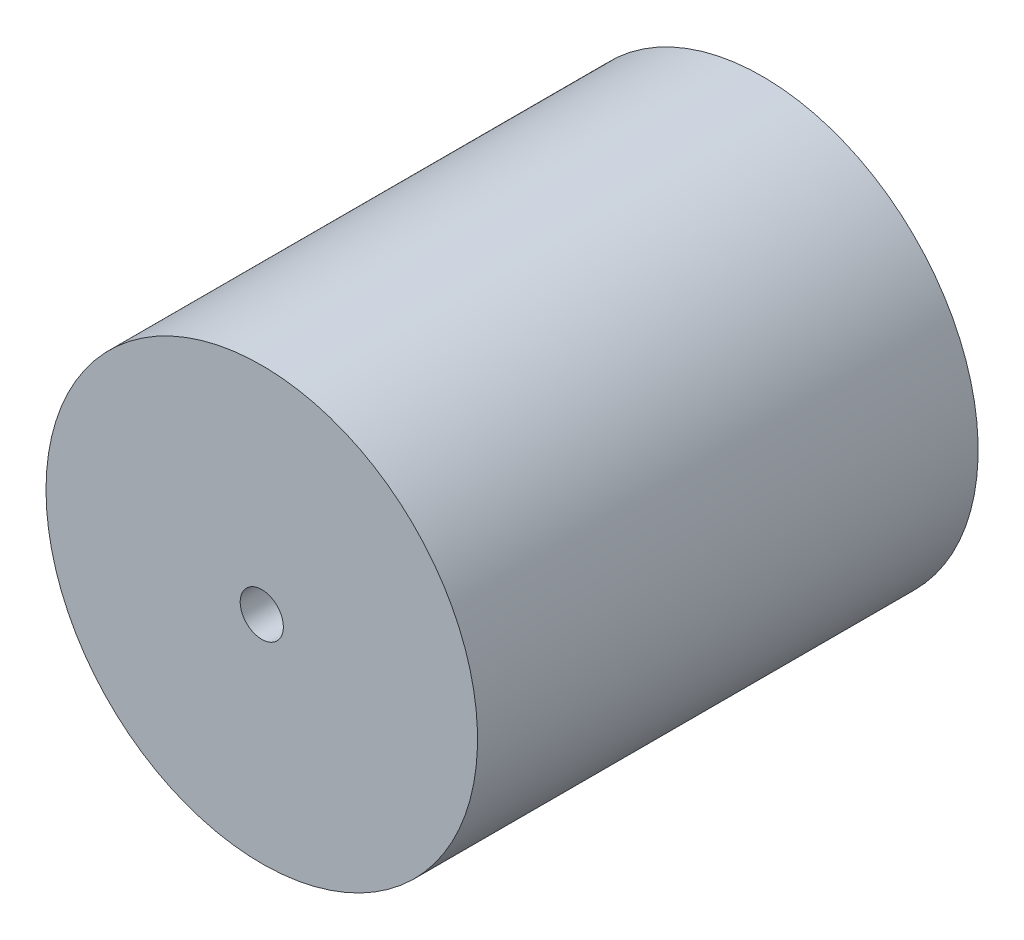
SolidWorks part; units mm, degrees
ref_plane "Front Plane" through (0, 0, 0) normal (0, 0, 1) x (1, 0, 0)
ref_plane "Top Plane" through (0, 0, 0) normal (0, 1, 0) x (1, 0, 0)
ref_plane "Right Plane" through (0, 0, 0) normal (1, 0, 0) x (0, 0, -1)
sketch "Sketch1" plane through (0, 0, 0) normal (0, 0, 1) x (1, 0, 0)
  circle A0 centre (0, 0) radius 12.5
  dimension "D1" = 25
extrude "Boss-Extrude1" add sketch "Sketch1" along normal blind 29
sketch "Sketch2" plane through (0, 0, 29) normal (0, 0, 1) x (1, 0, 0)
  point P0 (0, 0)
hole_wizard "M3x0.5 Tapped Hole1" positions "Sketch3" profile "Sketch5" tap size "M3x0.5" standard "ANSI Metric"
sketch "Sketch3" plane through (0, 0, 29) normal (0, 0, 1) x (1, 0, 0)
  point P0 (0, 0)
sketch "Sketch5" plane through (0, 0, 29) normal (1, 0, 0) x (0, -1, 0)
  line L0 (0, 0) -> (0, 20.7511)
  line L1 (0, 20.7511) -> (1.25, 20)
  line L2 (1.25, 20) -> (1.25, 0)
  line L5 (1.25, 0) -> (0, 0)
  line L10 (0, 20.7511) -> (-1.25, 20) construction
  line L11 (0, -6.35) -> (0, 107.95) construction
  dimension "Tap Drill Dia." = 2.5
  dimension "Tap Drill Depth" = 20
  dimension "Drill Angle" = 118
cosmetic thread "Hole Thread1"
